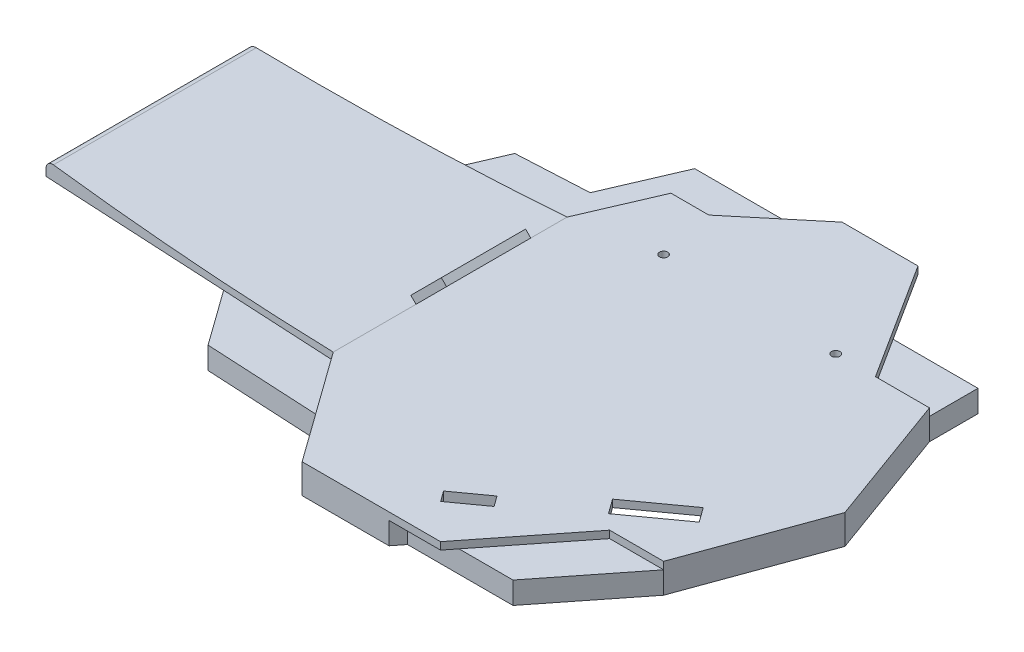
SolidWorks part; units mm, degrees
ref_plane "前视基准面" through (0, 0, 0) normal (0, 0, 1) x (1, 0, 0)
ref_plane "上视基准面" through (0, 0, 0) normal (0, 1, 0) x (1, 0, 0)
ref_plane "右视基准面" through (0, 0, 0) normal (1, 0, 0) x (0, 0, -1)
other "Configuration Table"
sketch "草图2" plane through (0, 0, 0) normal (0, 1, 0) x (1, 0, 0)
  line L0 (0, 0) -> (243.6421, 0) construction
  line L30 (176.8295, 36.1855) -> (82.5273, -31.8251) construction
  line L35 (141.8216, 68.0827) -> (121.1619, 68.0827)
  line L36 (176.8295, 36.1855) -> (190, 0)
  line L37 (104.1466, -61.9173) -> (82.5273, -31.8251)
  line L38 (82.5273, -31.8251) -> (0, -27.5)
  line L39 (0, -27.5) -> (0, 27.5)
  line L40 (0, 27.5) -> (82.5273, 31.8251)
  line L43 (190, 0) -> (176.8295, -36.1855)
  line L45 (82.5273, 31.8251) -> (91.0398, 51.6089)
  line L51 (104.1466, -61.9173) -> (190, 0) construction
  line L53 (141.8216, -61.9173) -> (104.1466, -61.9173)
  line L55 (82.5273, 31.8251) -> (342.4089, 31.8251) construction
  line L57 (176.8295, 36.1855) -> (176.8295, 0) construction
  line L58 (176.8295, 0) -> (176.8295, -36.1855) construction
  line L59 (82.5273, -31.8251) -> (342.4089, -31.8251) construction
  line L62 (91.0398, 51.6089) -> (101.351, 51.6089)
  line L63 (101.351, 51.6089) -> (121.1619, 68.0827)
  line L64 (141.8216, 68.0827) -> (162.1337, 36.1855)
  line L65 (162.1337, 36.1855) -> (176.8295, 36.1855)
  line L66 (176.8295, -36.1855) -> (162.1337, -36.1855)
  line L67 (162.1337, -36.1855) -> (141.8216, -61.9173)
  dimension "D1" = 190
  dimension "D2" = 130
  dimension "D4" = 55
  dimension "D6" = 93
  dimension "D7" = 93
  dimension "D8" = 140
extrude "凸台-拉伸1" add sketch "草图2" along normal blind 2
sketch "草图6" plane through (0, 2, 0) normal (0, 1, 0) x (1, 0, 0)
  line L0 (82.5273, 31.8251) -> (82.5273, -31.8251)
  line L1 (82.5273, -31.8251) -> (0, -27.5)
  line L2 (0, -27.5) -> (0, 27.5)
  line L3 (0, 27.5) -> (82.5273, 31.8251)
extrude "凸台-拉伸2" add sketch "草图6" along normal blind 2
sketch "草图7" plane through (0, 0, 0) normal (0, 0, 1) x (1, 0, 0)
  line L2 (82.5273, 2) -> (82.5273, 30.7408)
  line L3 (82.5273, 30.7408) -> (0, 4)
  spline S0 degree 2 poles (82.5273, 2) (41.2153, 1.0012) (0, 4) knots 0 0 0 1 1 1
extrude "切除-拉伸3" cut sketch "草图7" against normal through all both and the other way through all
fillet "圆角1" radius 2 1 edges at (0, 4, 0)
ref_plane "基准面3" through (0, -12, 0) normal (0, -1, 0) x (-1, 0, 0)
sketch "草图10" plane through (0, 0, 0) normal (0, -1, 0) x (1, 0, 0)
  line L0 (0, 27.5) -> (82.5273, 31.8251)
  line L1 (82.5273, 31.8251) -> (171.8529, 31.8251)
  line L2 (171.8529, 31.8251) -> (171.8529, -31.8251)
  line L3 (171.8529, -31.8251) -> (82.5273, -31.8251)
  line L4 (82.5273, -31.8251) -> (0, -27.5)
  line L5 (0, -27.5) -> (0, 27.5)
sketch "草图12" plane through (0, 2, 0) normal (0, 1, 0) x (1, 0, 0)
  line L0 (176.8295, 36.1855) -> (82.5273, -31.8251)
  line L1 (190, 0) -> (104.1466, -61.9173)
  line L2 (183.4148, 18.0928) -> (93.337, -46.8712) construction
  line L3 (190, 0) -> (176.8295, 36.1855) construction
  line L4 (82.5273, -31.8251) -> (104.1466, -61.9173) construction
sketch "草图13" plane through (0, 0, 0) normal (0, -1, 0) x (1, 0, 0)
  line L0 (53.5015, -30.3039) -> (58.4123, -41.717)
  line L1 (82.5273, -31.8251) -> (0, -27.5) construction
  line L2 (58.4123, -41.717) -> (77.9269, -42.7397)
  line L3 (77.9269, -42.7397) -> (86.4844, -62.6282)
  line L4 (86.4844, -62.6282) -> (136.1647, -62.6282)
  line L5 (176.8295, 36.1855) -> (190, 0)
  line L6 (190, 0) -> (176.8295, -36.1855)
  line L7 (136.1647, -62.6282) -> (144.5841, -49.4069)
  line L8 (144.5841, -49.4069) -> (176.8295, -49.4069)
  line L9 (176.8295, -49.4069) -> (176.8295, -36.1855)
  line L11 (176.8295, 36.1855) -> (158.7432, 59.0976)
  line L12 (158.7432, 59.0976) -> (130.0164, 59.0976)
  line L13 (130.0164, 59.0976) -> (127.7906, 61.9173)
  line L14 (104.1466, 61.9173) -> (141.8216, 61.9173) construction
  line L15 (127.7906, 61.9173) -> (104.1466, 61.9173)
  line L16 (104.1466, 61.9173) -> (93.337, 46.8712)
  line L17 (93.337, 46.8712) -> (61.8459, 45.2208)
  line L18 (61.8459, 45.2208) -> (51.0363, 30.1747)
  line L19 (0, 27.5) -> (82.5273, 31.8251) construction
  line L20 (51.0363, 30.1747) -> (171.8529, 31.8251)
  line L21 (171.8529, 31.8251) -> (171.8529, -31.8251)
  line L22 (171.8529, -31.8251) -> (53.5015, -30.3039)
extrude "凸台-拉伸4" add sketch "草图13" along normal blind 6 contours L18 L20 L21 L22 L0 L2 L3 L4 L7 L8 L9 L6 L5 L11 L12 L13 L15 L16 L17
sketch "草图15" plane through (0, 2, 0) normal (0, 1, 0) x (1, 0, 0)
  circle A0 centre (151.351, 36.16) radius 1.1
  circle A1 centre (104.4979, 36.16) radius 1.06
  point P0 (151.351, 36.16)
  point P3 (104.4979, 36.16)
hole_wizard "#4-40 螺纹孔2" positions "草图15" profile "草图16" tap size "#4-40" standard "ANSI Inch" end condition through all
sketch "草图16" plane through (151.351, 2, -36.16) normal (1, 0, 0) x (0, 0, 1)
  line L0 (0, 0) -> (0, 8)
  line L1 (0, 8) -> (1.1303, 8)
  line L2 (1.1303, 8) -> (1.1303, 0)
  line L5 (1.1303, 0) -> (0, 0)
  line L11 (0, -6.35) -> (0, 107.95) construction
  dimension "通孔螺纹孔钻头直径" = 2.2606
  dimension "通孔螺纹孔钻头深度" = 8
cosmetic thread "孔螺纹线2" parameters "D2"=2.8448
cosmetic thread "孔螺纹线3" parameters "D2"=2.8448
sketch "草图17" plane through (0, 2, 0) normal (0, 1, 0) x (1, 0, 0)
  line L1 (127.9245, 6.0352) -> (127.9245, 66.2872) construction
  line L2 (127.9245, 71.5706) -> (127.9245, 3.7208) construction
  line L3 (116.0112, 26.5953) -> (142.1812, 26.5953)
  arc A1 (116.0112, 26.5953) -> (142.1812, 26.5953) centre (129.0962, 34.7996) ccw
sketch "草图18" plane through (0, 2, 0) normal (0, 1, 0) x (1, 0, 0)
  line L4 (169.5639, -18.1259) -> (155.2183, -28.4719)
  line L5 (172.4314, -22.1019) -> (169.5639, -18.1259)
  line L6 (158.0858, -32.4479) -> (172.4314, -22.1019)
  line L7 (155.2183, -28.4719) -> (158.0858, -32.4479)
  line L8 (169.5639, -18.1259) -> (155.2183, -28.4719)
  line L9 (172.4314, -22.1019) -> (169.5639, -18.1259)
  line L10 (158.0858, -32.4479) -> (172.4314, -22.1019)
  line L11 (155.2183, -28.4719) -> (158.0858, -32.4479)
  line L12 (130.3021, -49.5646) -> (132.3616, -52.4203)
  line L13 (132.3616, -52.4203) -> (140.8147, -46.3239)
  line L14 (140.8147, -46.3239) -> (138.7552, -43.4683)
  line L15 (138.7552, -43.4683) -> (130.3021, -49.5646)
  line L16 (130.3021, -49.5646) -> (132.3616, -52.4203)
  line L17 (132.3616, -52.4203) -> (140.8147, -46.3239)
  line L18 (140.8147, -46.3239) -> (138.7552, -43.4683)
  line L19 (138.7552, -43.4683) -> (130.3021, -49.5646)
  dimension "D1" = 0
  dimension "D2" = 0
extrude "切除-拉伸7" cut sketch "草图18" against normal through all
sketch "草图19" plane through (0, 2, 0) normal (0, 1, 0) x (1, 0, 0)
  line L0 (82.5273, -31.8251) -> (176.8295, 36.1855)
  line L1 (176.8295, 36.1855) -> (190, 0)
  line L2 (190, 0) -> (104.1466, -61.9173)
  line L3 (104.1466, -61.9173) -> (82.5273, -31.8251)
ref_plane "基准面4" through (40.2637, -40.2637, 0) normal (-0.7071, 0.7071, 0) x (0, 0, -1)
sketch "草图23" plane through (40.2637, -40.2637, 0) normal (-0.7071, 0.7071, 0) x (0, 0, -1)
  line L0 (-9.292, -59.7699) -> (13.6381, -59.7699)
  line L1 (-31.8251, -59.7699) -> (31.8251, -59.7699) construction
  line L2 (13.6381, -59.7699) -> (13.6381, -71.5206)
  line L3 (13.6381, -71.5206) -> (-9.292, -71.5206)
  line L4 (-9.292, -71.5206) -> (-9.292, -60.8098)
  line L5 (-9.292, -60.8098) -> (-9.292, -59.7699)
  point P7 (0, 0)
extrude "凸台-拉伸5" add sketch "草图23" along normal blind 2 separate body
